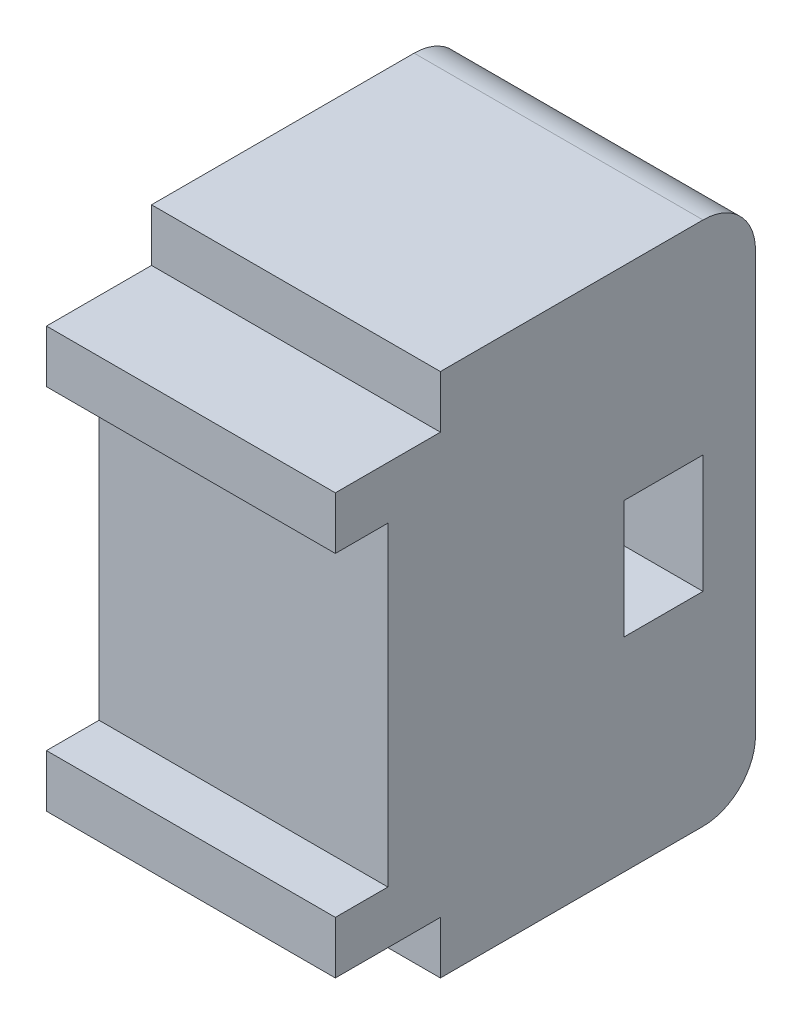
SolidWorks part; units mm, degrees
ref_plane "Front Plane" through (0, 0, 0) normal (1, 0, 0) x (0, 1, 0)
ref_plane "Top Plane" through (0, 0, 0) normal (0, 0, 1) x (0, 1, 0)
ref_plane "Right Plane" through (0, 0, 0) normal (0, 1, 0) x (-1, 0, 0)
sketch "Sketch1" plane through (0, 0, 0) normal (1, 0, 0) x (0, 1, 0)
  line L1 (-10, 6) -> (10, 6)
  line L2 (-10, 6) -> (-10, -6)
  line L3 (-10, -6) -> (10, -6)
  line L4 (10, 6) -> (10, -6)
  line L5 (-10, 6) -> (10, -6) construction
  line L6 (-10, -6) -> (10, 6) construction
  point P0 (0, 0)
  dimension "D1" = 12
  dimension "D2" = 20
extrude "Boss-Extrude1" add sketch "Sketch1" along normal blind 11
sketch "Sketch5" plane through (0, 0, 0) normal (0, 0, 1) x (0, 1, 0)
  line L0 (10, 0) -> (-10, 0) construction
  line L1 (-8, 0) -> (8, 0)
  line L2 (-8, 0) -> (-8, -11)
  line L3 (-8, -11) -> (8, -11)
  line L4 (8, 0) -> (8, -11)
  line L5 (-10, -11) -> (-10, 0) construction
  line L6 (10, -11) -> (10, 0) construction
  line L7 (10, -11) -> (-10, -11) construction
  dimension "D1" = 2
  dimension "D2" = 2
  dimension "D3" = 0
extrude "Boss-Extrude2" add sketch "Sketch5" along normal blind 8
fillet "Fillet1" radius 2 2 edges at (5.5, 10, -6) (5.5, -10, -6)
sketch "Sketch7" plane through (0, 0, 0) normal (1, 0, 0) x (0, 1, 0)
  line L0 (-2.25, -4) -> (2.25, -4)
  line L2 (-2.25, -1) -> (2.25, -1)
  line L3 (-2.25, -1) -> (-2.25, -4)
  line L5 (2.25, -1) -> (2.25, -4)
  line L6 (-8, -6) -> (8, -6) construction
  dimension "D1" = 3
  dimension "D2" = 4.5
  dimension "D3" = 2
extrude "Cut-Extrude1" cut sketch "Sketch7" along normal blind 15
sketch "Sketch9" plane through (0, 0, 8) normal (0, 0, 1) x (1, 0, 0)
  line L0 (0, -8) -> (11, -8) construction
  line L1 (0, 8) -> (11, 8)
  line L2 (0, 8) -> (0, 6)
  line L3 (0, -8) -> (11, -8)
  line L4 (11, 8) -> (11, 6)
  line L5 (0, -8) -> (11, -8) construction
  line L6 (0, 6) -> (11, 6)
  line L7 (0, -6) -> (0, -8)
  line L8 (0, -6) -> (11, -6)
  line L9 (11, -6) -> (11, -8)
  dimension "D1" = 2
  dimension "D2" = 2
  dimension "D3" = 11
extrude "Boss-Extrude4" add sketch "Sketch9" along normal blind 2
